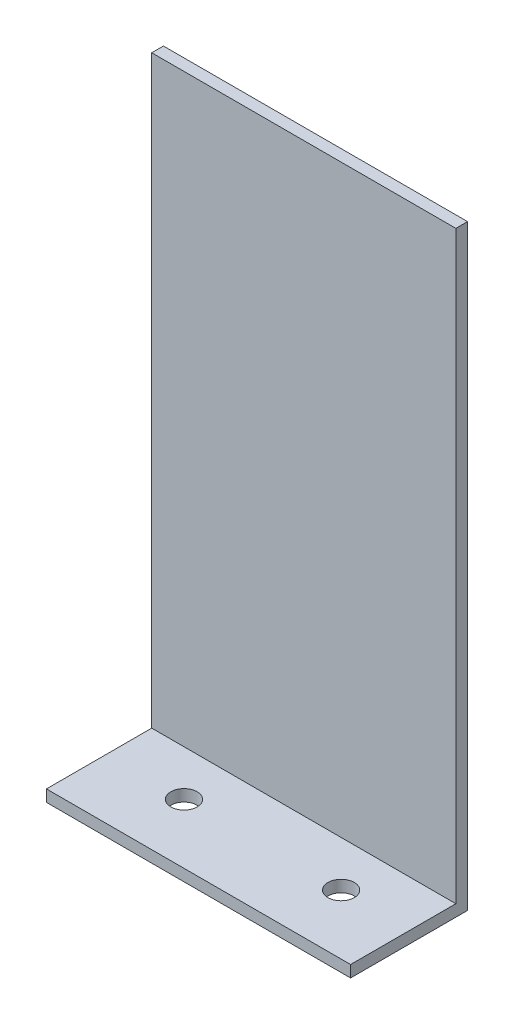
SolidWorks part; units mm, degrees
ref_plane "Plan de face" through (0, 0, 0) normal (0, 0, 1) x (1, 0, 0)
ref_plane "Plan de dessus" through (0, 0, 0) normal (0, 1, 0) x (1, 0, 0)
ref_plane "Plan de droite" through (0, 0, 0) normal (1, 0, 0) x (0, 0, -1)
sketch "Esquisse1" plane through (0, 0, 0) normal (0, 0, 1) x (1, 0, 0)
  line L1 (-26, -51) -> (26, -51)
  line L2 (-26, -51) -> (-26, 51)
  line L3 (-26, 51) -> (26, 51)
  line L4 (26, -51) -> (26, 51)
  line L5 (-26, -51) -> (26, 51) construction
  line L6 (-26, 51) -> (26, -51) construction
  point P0 (0, 0)
  dimension "D1" = 52
  dimension "D2" = 102
extrude "Boss.-Extru.1" add sketch "Esquisse1" along normal blind 20
sketch "Esquisse2" plane through (0, 51, 0) normal (0, 1, 0) x (1, 0, 0)
  line L8 (24, -2) -> (-24, -2)
  line L9 (-24, -2) -> (-24, -18)
  line L10 (-24, -18) -> (24, -18)
  line L11 (24, -18) -> (24, -2)
  line L12 (34.4102, -2) -> (-31.5984, -2)
  line L13 (-31.5984, -2) -> (-31.5984, -42.9462)
  line L14 (-31.5984, -42.9462) -> (34.4102, -42.9462)
  line L15 (34.4102, -42.9462) -> (34.4102, -2)
  dimension "D1" = 2
extrude "Enlèv. mat.-Extru.1" cut sketch "Esquisse2" against normal blind 100
hole_wizard "Dégagement M42" positions "Esquisse7" profile "Esquisse6" hole size "M4" standard "JIS" end condition through all
sketch "Esquisse7" plane through (0, -49, 0) normal (0, 1, 0) x (1, 0, 0)
  point P0 (-12.6957, -9.7851)
  point P2 (14.163, -9.7851)
sketch "Esquisse6" plane through (-12.6957, -49, 9.7851) normal (1, 0, 0) x (0, 0, 1)
  line L0 (0, 0) -> (0, 2)
  line L1 (0, 2) -> (2.25, 2)
  line L2 (2.25, 2) -> (2.25, 0)
  line L5 (2.25, 0) -> (0, 0)
  line L11 (0, -6.35) -> (0, 107.95) construction
  dimension "Diamètre du perçage jusqu'au prochain" = 4.5
  dimension "Profondeur du perçage jusqu'au prochain" = 2
